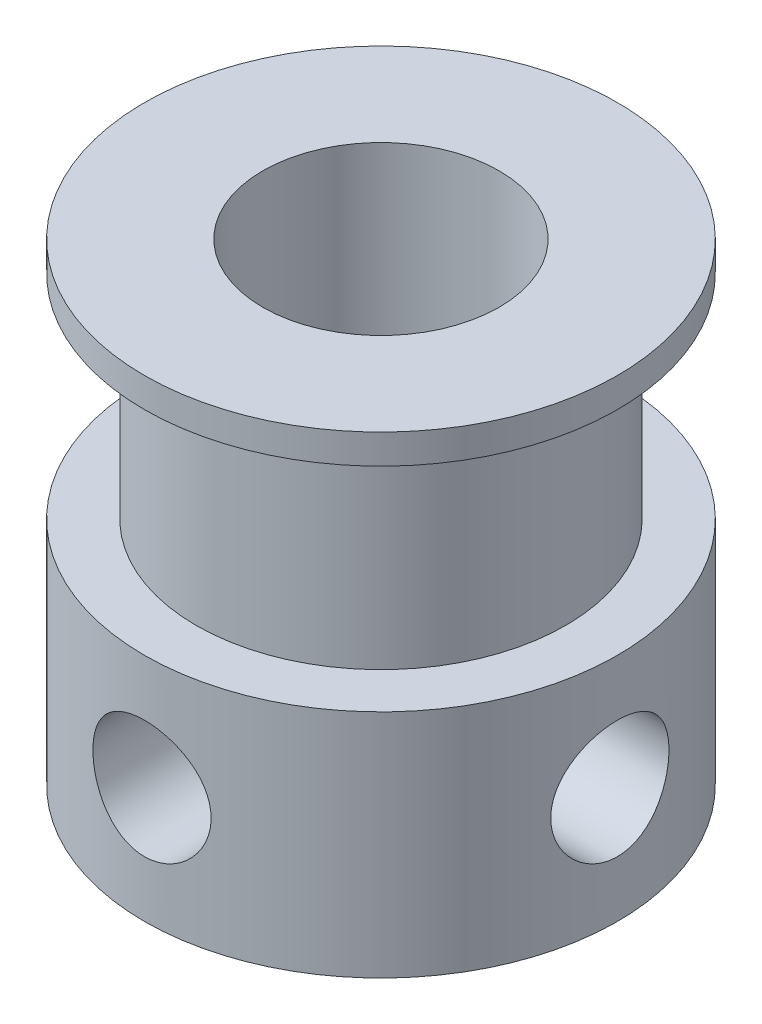
SolidWorks part; units mm, degrees
ref_plane "Front Plane" through (0, 0, 0) normal (0, 0, 1) x (1, 0, 0)
ref_plane "Top Plane" through (0, 0, 0) normal (0, 1, 0) x (1, 0, 0)
ref_plane "Right Plane" through (0, 0, 0) normal (1, 0, 0) x (0, 0, -1)
sketch "Sketch1" plane through (0, 0, 0) normal (0, 0, 1) x (1, 0, 0)
  line L0 (0, 17.6014) -> (0, -11.0259) construction
  line L1 (-4, 0) -> (-8, 0)
  line L9 (-8, 16) -> (-4, 16)
  line L10 (-4, 16) -> (-4, 0)
  line L11 (-8, 0) -> (-8, 7.8)
  line L12 (-8, 7.8) -> (-6.25, 7.8)
  line L13 (-6.25, 7.8) -> (-6.25, 15)
  line L14 (-6.25, 15) -> (-8, 15)
  line L15 (-8, 15) -> (-8, 16)
  point P5 (-7.125, 15)
  dimension "D1" = 7.2
  dimension "D2" = 1
  dimension "D3" = 8
  dimension "D4" = 12.5
  dimension "D5" = 16
  dimension "D7" = 16
revolve "Revolve1" add sketch "Sketch1" angle 360 about L0
hole_wizard "Ø4.0 (4) Diameter Hole1" positions "Sketch3" profile "Sketch2" hole size "Ø4.0" standard "ISO"
sketch "Sketch3" plane through (0, 0, 0) normal (0, 0, 1) x (1, 0, 0)
  line L0 (-8, 3.9) -> (13.4021, 3.9) construction
  line L1 (-8, 7.8) -> (-8, 0) construction
  point P4 (0, 3.9)
  point P16 (0, 0)
sketch "Sketch2" plane through (0, 3.9, 0) normal (1, 0, 0) x (0, -1, 0)
  line L0 (0, 0) -> (0, 8)
  line L1 (0, 8) -> (2, 8)
  line L2 (2, 8) -> (2, 0)
  line L5 (2, 0) -> (0, 0)
  line L11 (0, -6.35) -> (0, 107.95) construction
  dimension "Thru Hole Dia." = 4
  dimension "Thru Hole Depth" = 8
pattern_circular "CirPattern1" count 4 every 90 of "Ø4.0 (4) Diameter Hole1"
